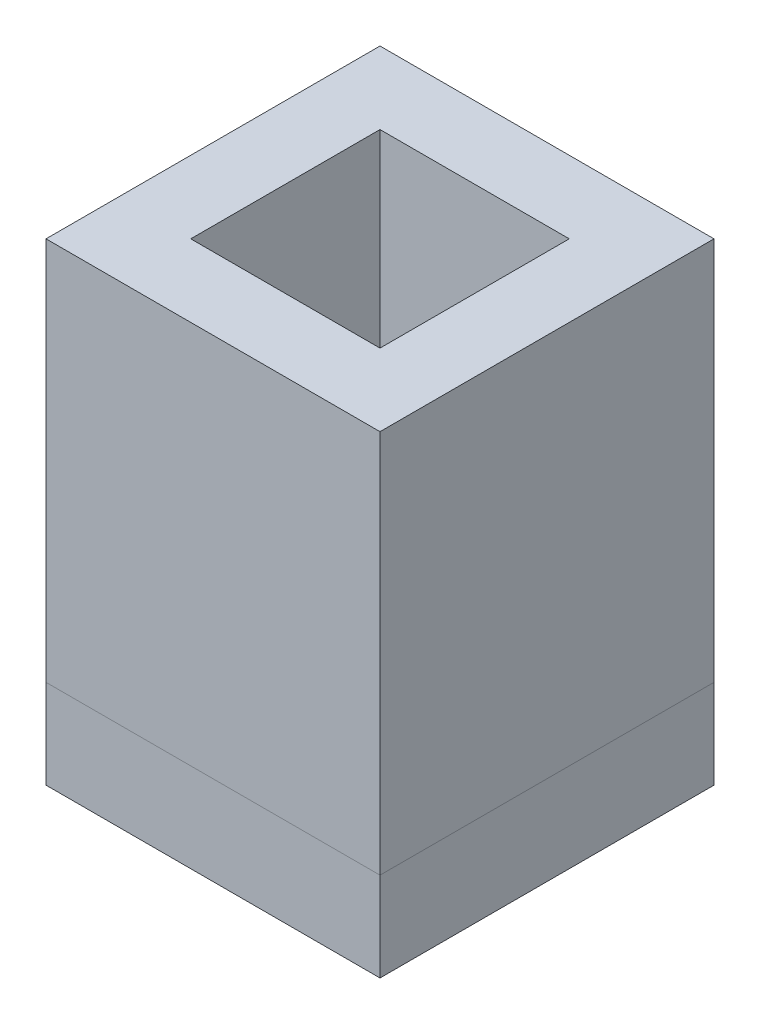
SolidWorks part; units mm, degrees
ref_plane "Front Plane" through (0, 0, 0) normal (0, 0, 1) x (1, 0, 0)
ref_plane "Top Plane" through (0, 0, 0) normal (0, 1, 0) x (1, 0, 0)
ref_plane "Right Plane" through (0, 0, 0) normal (1, 0, 0) x (0, 0, -1)
sketch "Sketch1" plane through (0, 0, 0) normal (0, 1, 0) x (1, 0, 0)
  line L1 (-150, -150) -> (150, -150)
  line L2 (-150, -150) -> (-150, 150)
  line L3 (-150, 150) -> (150, 150)
  line L4 (150, -150) -> (150, 150)
  line L5 (-150, -150) -> (150, 150) construction
  line L6 (-150, 150) -> (150, -150) construction
  point P0 (0, 0)
  dimension "D1" = 300
extrude "Boss-Extrude1" add sketch "Sketch1" along normal blind 80
sketch "Sketch2" plane through (0, 80, 0) normal (0, 1, 0) x (1, 0, 0)
  line L1 (-150, -150) -> (150, -150)
  line L2 (-150, -150) -> (-150, 150)
  line L3 (-150, 150) -> (150, 150)
  line L4 (150, -150) -> (150, 150)
  line L5 (-150, -150) -> (150, 150) construction
  line L6 (-150, 150) -> (150, -150) construction
  line L7 (-85, -85) -> (85, -85)
  line L8 (-85, -85) -> (-85, 85)
  line L9 (-85, 85) -> (85, 85)
  line L10 (85, -85) -> (85, 85)
  line L11 (-85, -85) -> (85, 85) construction
  line L12 (-85, 85) -> (85, -85) construction
  point P0 (0, 0)
  point P7 (0, 0)
  dimension "D1" = 65
extrude "Boss-Extrude2" add sketch "Sketch2" along normal blind 345 separate body
